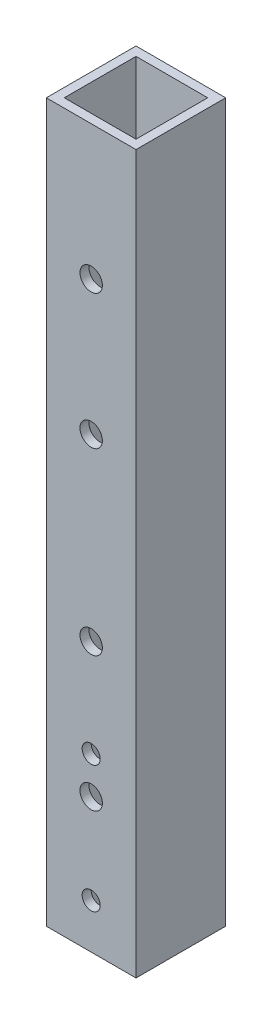
SolidWorks part; units mm, degrees
ref_plane "Front Plane" through (0, 0, 0) normal (0, 0, 1) x (1, 0, 0)
ref_plane "Top Plane" through (0, 0, 0) normal (0, 1, 0) x (1, 0, 0)
ref_plane "Right Plane" through (0, 0, 0) normal (1, 0, 0) x (0, 0, -1)
sketch "Sketch1" plane through (0, 0, 0) normal (0, 1, 0) x (1, 0, 0)
  line L1 (-12.7, 12.7) -> (12.7, 12.7)
  line L2 (-12.7, 12.7) -> (-12.7, -12.7)
  line L3 (-12.7, -12.7) -> (12.7, -12.7)
  line L4 (12.7, 12.7) -> (12.7, -12.7)
  line L5 (-12.7, 12.7) -> (12.7, -12.7) construction
  line L6 (-12.7, -12.7) -> (12.7, 12.7) construction
  line L7 (-10.16, 10.16) -> (10.16, 10.16)
  line L8 (-10.16, 10.16) -> (-10.16, -10.16)
  line L9 (-10.16, -10.16) -> (10.16, -10.16)
  line L10 (10.16, 10.16) -> (10.16, -10.16)
  line L11 (-10.16, 10.16) -> (10.16, -10.16) construction
  line L12 (-10.16, -10.16) -> (10.16, 10.16) construction
  point P0 (0, 0)
  point P6 (0, 0)
  dimension "D1" = 25.4
  dimension "D2" = 25.4
  dimension "D3" = 20.32
  dimension "D4" = 20.32
extrude "Boss-Extrude1" add sketch "Sketch1" along normal mid plane 203.2
sketch "Sketch4" plane through (0, 0, 12.7) normal (0, 0, 1) x (1, 0, 0)
  line L0 (-12.7, 101.6) -> (12.7, 101.6) construction
  line L1 (-12.7, -101.6) -> (12.7, -101.6) construction
  line L2 (12.7, 101.6) -> (12.7, -101.6) construction
  line L3 (-12.7, 101.6) -> (-12.7, -101.6) construction
  circle A0 centre (0, 63.5) radius 3.175
  circle A1 centre (0, -63.5) radius 3.175
  dimension "D1" = 38.1
  dimension "D2" = 38.1
  dimension "D3" = 6.35
  dimension "D4" = 12.7
  dimension "D5" = 12.7
extrude "Cut-Extrude3" cut sketch "Sketch4" against normal blind 25.4
sketch "Sketch5" plane through (0, 0, 12.7) normal (0, 0, 1) x (1, 0, 0)
  line L0 (-12.7, 101.6) -> (-12.7, -101.6) construction
  line L1 (-12.7, 101.6) -> (12.7, 101.6) construction
  line L2 (-12.7, -101.6) -> (12.7, -101.6) construction
  circle A0 centre (0, 25.4) radius 3.175
  circle A1 centre (0, -25.4) radius 3.175
  dimension "D1" = 6.35
  dimension "D2" = 12.7
  dimension "D3" = 12.7
  dimension "D4" = 76.2
  dimension "D5" = 76.2
extrude "Cut-Extrude4" cut sketch "Sketch5" against normal blind 25.4
sketch "Sketch6" plane through (0, 0, 12.7) normal (0, 0, 1) x (1, 0, 0)
  line L1 (-12.7, 101.6) -> (-12.7, -101.6) construction
  line L2 (-12.7, -101.6) -> (12.7, -101.6) construction
  circle A0 centre (0, -88.9) radius 1.27
  circle A1 centre (0, -52.959) radius 1.27
  dimension "D1" = 12.7
  dimension "D2" = 12.7
  dimension "D3" = 2.54
  dimension "D4" = 35.941
extrude "Cut-Extrude6" cut sketch "Sketch6" against normal blind 25.4
hole_wizard "#10 Clearance Hole1" positions "Sketch7" profile "Sketch8" hole size "#10" standard "ANSI Inch" end condition through all
sketch "Sketch7" plane through (0, 0, -12.7) normal (0, 0, -1) x (-1, 0, 0)
  point P0 (0, -52.959)
  point P3 (0, -88.9)
sketch "Sketch8" plane through (0, -52.959, -12.7) normal (1, 0, 0) x (0, 1, 0)
  line L0 (0, 0) -> (0, 25.4)
  line L1 (0, 25.4) -> (2.5527, 25.4)
  line L2 (2.5527, 25.4) -> (2.5527, 0)
  line L5 (2.5527, 0) -> (0, 0)
  line L11 (0, -6.35) -> (0, 107.95) construction
  dimension "Thru Hole Dia." = 5.1054
  dimension "Thru Hole Depth" = 25.4
